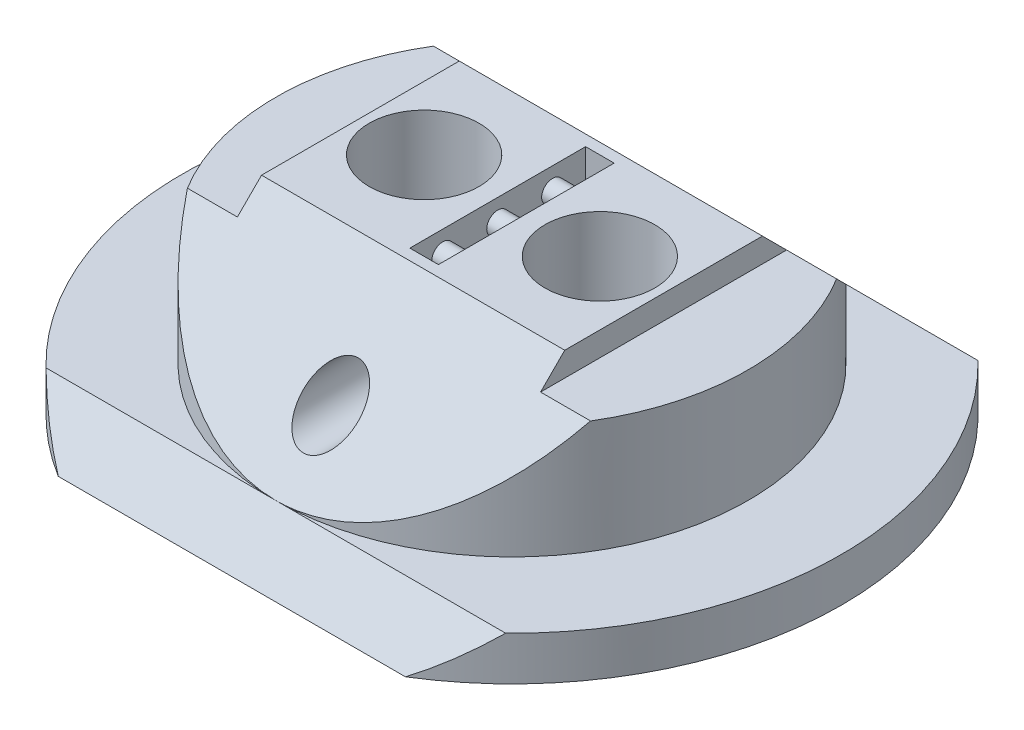
SolidWorks part; units mm, degrees
ref_plane "Front Plane" through (0, 0, 0) normal (0, 0, 1) x (1, 0, 0)
ref_plane "Top Plane" through (0, 0, 0) normal (0, 1, 0) x (1, 0, 0)
ref_plane "Right Plane" through (0, 0, 0) normal (1, 0, 0) x (0, 0, -1)
sketch "Sketch1" plane through (0, 0, 0) normal (0, 1, 0) x (1, 0, 0)
  circle A0 centre (0, 0) radius 30
extrude "Boss-Extrude1" add sketch "Sketch1" along normal blind 4
sketch "Sketch2" plane through (0, 0, 0) normal (1, 0, 0) x (0, 0, -1)
  line L0 (0, 4) -> (21.5, 4)
  line L1 (30, 4) -> (-30, 4) construction
  line L3 (0, 4) -> (-21.5, 4)
  line L5 (0, 4) -> (0, 19.5) construction
  line L6 (-9, 16.5) -> (-21.5, 4)
  line L7 (-9, 16.5) -> (9, 16.5)
  line L9 (9, 16.5) -> (21.5, 4)
  dimension "D1" = 12.5
  dimension "D2" = 45
  dimension "D3" = 21.5
  dimension "D4" = 21.5
  dimension "D5" = 45
sketch "Sketch3" plane through (0, 4, 0) normal (0, 1, 0) x (1, 0, 0)
  circle A0 centre (0, 0) radius 21.5
  dimension "D1" = 43
extrude "Boss-Extrude2" add sketch "Sketch2" along normal up to surface and the other way up to surface up to face at (0, 4, 30) other way up to face at (0, 4, 30)
ref_plane "Plane1" through (0, 12.75, -12.75) normal (0, 0.7071, -0.7071) x (1, 0, 0)
other "SurfaceCut1"
ref_plane "Plane2" through (0, 12.75, 12.75) normal (0, 0.7071, 0.7071) x (1, 0, 0)
other "SurfaceCut2"
extrude "Cut-Extrude2" cut sketch "Sketch3" against normal up to surface (12.5 mm away) flip side to cut contours A0
sketch "Sketch5" plane through (0, 0, 0) normal (0, -1, 0) x (-1, 0, 0)
  line L0 (0, 0) -> (0, -6)
  line L1 (0, -6) -> (-17.5, -6)
  line L2 (-17.5, -6) -> (-17.5, 6)
  line L3 (-17.5, 6) -> (17.5, 6)
  line L4 (17.5, 6) -> (17.5, -6)
  line L5 (17.5, -6) -> (0, -6)
  circle A0 centre (0, 0) radius 6
  circle A1 centre (0, 0) radius 3.5
  dimension "D1" = 12
  dimension "D2" = 7
  dimension "D3" = 12
  dimension "D4" = 6
  dimension "D5" = 35
  dimension "D6" = 17.5
extrude "Boss-Extrude3" add sketch "Sketch5" along normal blind 18 contours L1 L2 L3 L4 L5
sketch "Sketch6" plane through (0, 0, 0) normal (0, -1, 0) x (1, 0, 0)
  line L0 (0, 6) -> (0, 15) construction
  line L1 (-17.5, 6) -> (17.5, 6) construction
  line L2 (0, 15) -> (7, 15)
  line L3 (7, 15) -> (7, 6)
  line L4 (-17.5, 6) -> (17.5, 6) construction
  line L5 (7, 6) -> (-7, 6)
  line L6 (-7, 6) -> (-7, 15)
  line L7 (-7, 15) -> (0, 15)
  dimension "D1" = 14
  dimension "D2" = 9
extrude "Boss-Extrude4" add sketch "Sketch6" along normal blind 15 contours L7 L2 L3 L5 L6
sketch "Sketch7" plane through (0, 0, 0) normal (0, -1, 0) x (1, 0, 0)
  line L0 (0, -6) -> (0, -15) construction
  line L1 (17.5, -6) -> (-17.5, -6) construction
  line L2 (0, -15) -> (7, -15)
  line L3 (7, -15) -> (7, -6)
  line L4 (7, -6) -> (-7, -6)
  line L7 (-7, -6) -> (-7, -15)
  line L8 (-7, -15) -> (0, -15)
  dimension "D1" = 9
  dimension "D2" = 14
extrude "Boss-Extrude5" add sketch "Sketch7" along normal blind 15
sketch "Sketch8" plane through (0, 0, 0) normal (0, 0, 1) x (1, 0, 0)
  line L0 (0, 0) -> (12.5, 0) construction
  line L1 (12.5, 0) -> (12.5, -12.5) construction
  line L2 (12.5, -12.5) -> (-12.5, -12.5) construction
  line L3 (-12.5, -12.5) -> (-12.5, 0) construction
  line L4 (-12.5, 0) -> (0, 0) construction
  circle A0 centre (-12.5, -12.5) radius 2
  circle A1 centre (12.5, -12.5) radius 2
  dimension "D4" = 4
  dimension "D5" = 4
  dimension "D1" = 12.5
  dimension "D2" = 25
  dimension "D3" = 12.5
extrude "Cut-Extrude3" cut sketch "Sketch8" against normal through all both and the other way through all contours A0 | A1
ref_plane "Plane3" through (0, -18, 0) normal (0, -1, 0) x (-1, 0, 0)
ref_plane "Plane4" through (10.366, -9.6749, -8.0624) normal (0.6355, -0.5931, -0.4943) x (-0.3613, 0.3373, -0.8693)
ref_plane "Plane5" through (-10.366, -9.6749, -8.0624) normal (0.6355, 0.5931, 0.4943) x (0.3613, 0.3373, -0.8693)
ref_plane "Plane6" through (10.366, -9.6749, 8.0624) normal (-0.6355, 0.5931, -0.4943) x (-0.3613, 0.3373, 0.8693)
ref_plane "Plane7" through (-10.366, -9.6749, 8.0624) normal (0.6355, 0.5931, -0.4943) x (-0.3613, -0.3373, -0.8693)
ref_plane "Plane9" through (0, 0, 6) normal (0, 0, 1) x (1, 0, 0)
sketch "Sketch16" plane through (0, 0, 6) normal (0, 0, 1) x (1, 0, 0)
  line L0 (17.5, -18) -> (17.5, -14.5)
  line L1 (-6.6, -18) -> (6.6, -18) construction
  line L2 (17.5, -18) -> (17.5, 0) construction
  line L3 (17.5, -18) -> (14, -18)
  line L4 (17.5, -14.5) -> (14, -18)
  line L5 (-17.5, -18) -> (-14, -18)
  line L6 (-17.5, -18) -> (-17.5, 0) construction
  line L7 (-14, -18) -> (-17.5, -14.5)
  line L8 (-17.5, -14.5) -> (-17.5, -18)
  dimension "D2" = 3.5
extrude "Cut-Extrude8" cut sketch "Sketch16" against normal through all both and the other way through all
sketch "Sketch17" plane through (10.366, -9.6749, -8.0624) normal (0.6355, -0.5931, -0.4943) x (-0.3613, 0.3373, -0.8693)
  line L0 (-2.3725, -6.1896) -> (7.9806, -0.7067)
  line L1 (5.4512, -6.1896) -> (10.5101, 4.7762) construction
  line L2 (7.9806, -0.7067) -> (7.9806, -10.9658)
  line L3 (10.5101, -15.7421) -> (5.4512, -6.1896) construction
  line L4 (7.9806, -10.9658) -> (-2.3725, -6.1896)
extrude "Cut-Extrude9" cut sketch "Sketch17" along normal through all
sketch "Sketch19" plane through (-10.366, -9.6749, -8.0624) normal (0.6355, 0.5931, 0.4943) x (0.3613, 0.3373, -0.8693)
  line L0 (-2.3725, -6.1896) -> (7.9806, -10.9658)
  line L1 (7.9806, -10.9658) -> (7.9806, -0.7067)
  line L2 (5.4512, -6.1896) -> (10.5101, 4.7762) construction
  line L3 (7.9806, -0.7067) -> (-2.3725, -6.1896)
extrude "Cut-Extrude11" cut sketch "Sketch19" against normal blind 20 contours L3 L0 L1
sketch "Sketch20" plane through (-10.366, -9.6749, 8.0624) normal (0.6355, 0.5931, -0.4943) x (-0.3613, -0.3373, -0.8693)
  line L0 (2.3725, -6.1896) -> (-7.9806, -0.7067)
  line L1 (-5.4512, -6.1896) -> (-10.5101, 4.7762) construction
  line L2 (-7.9806, -0.7067) -> (-7.9806, -10.9658)
  line L3 (-5.4512, -6.1896) -> (-10.5101, -15.7421) construction
  line L4 (-7.9806, -10.9658) -> (2.3725, -6.1896)
extrude "Cut-Extrude12" cut sketch "Sketch20" against normal blind 20
sketch "Sketch21" plane through (10.366, -9.6749, 8.0624) normal (-0.6355, 0.5931, -0.4943) x (-0.3613, 0.3373, 0.8693)
  line L0 (-2.3725, -6.1896) -> (7.9806, -0.7067)
  line L1 (5.4512, -6.1896) -> (10.5101, 4.7762) construction
  line L2 (7.9806, -0.7067) -> (7.9806, -10.9658)
  line L3 (7.9806, -10.9658) -> (-2.3725, -6.1896)
extrude "Cut-Extrude13" cut sketch "Sketch21" against normal blind 20 contours L0 L2 L3
ref_plane "Plane10" through (0, 16.5, 0) normal (0, 1, 0) x (1, 0, 0)
sketch "Sketch25" plane through (0, 0, 0) normal (0, 0, 1) x (1, 0, 0)
  line L1 (-33.0377, 0) -> (33.0377, 0)
  line L2 (-33.0377, 0) -> (-33.0377, -20.1422)
  line L3 (-33.0377, -20.1422) -> (33.0377, -20.1422)
  line L4 (33.0377, 0) -> (33.0377, -20.1422)
  dimension "D1" = 20.1422
  dimension "D2" = 66.0754
extrude "Cut-Extrude14" cut sketch "Sketch25" along normal through all both and the other way through all
sketch "Sketch26" plane through (0, 16.5, 0) normal (0, 1, 0) x (1, 0, 0)
  line L0 (-9.075, 0) -> (9.075, 0) construction
  circle A0 centre (-8, 0) radius 5
  circle A2 centre (8, 0) radius 5
  dimension "D1" = 10
  dimension "D2" = 10
  dimension "D3" = 8
  dimension "D4" = 8
extrude "Cut-Extrude15" cut sketch "Sketch26" against normal blind 24
sketch "Sketch29" plane through (0, 0, 6) normal (0, 0, 1) x (1, 0, 0)
  line L0 (21.5, 4) -> (21.5, 16.5) construction
  line L1 (21.5, 14.3) -> (13.8, 14.3)
  line L2 (21.5, 14.3) -> (21.5, 16.5)
  line L3 (21.5, 16.5) -> (13.8, 16.5)
  line L4 (13.8, 14.3) -> (13.8, 16.5)
  line L5 (9.9, 16.5) -> (-9.9, 16.5) construction
  dimension "D1" = 2.2
  dimension "D2" = 7.7
extrude "Cut-Extrude17" cut sketch "Sketch29" against normal through all both and the other way through all
sketch "Sketch31" plane through (0, 0, 6) normal (0, 0, 1) x (1, 0, 0)
  line L0 (-21.5, 16.5) -> (-21.5, 4) construction
  line L1 (-21.5, 14.3) -> (-13.8, 14.3)
  line L2 (-21.5, 14.3) -> (-21.5, 16.5)
  line L3 (-21.5, 16.5) -> (-13.8, 16.5)
  line L4 (-13.8, 14.3) -> (-13.8, 16.5)
  line L5 (9.9, 16.5) -> (-9.9, 16.5) construction
  dimension "D1" = 2.2
  dimension "D2" = 7.7
extrude "Cut-Extrude18" cut sketch "Sketch31" against normal through all both and the other way through all
sketch "Sketch33" plane through (0, 0, 0) normal (0, 0, 1) x (1, 0, 0)
  line L0 (0, -9.075) -> (0, 9.075) construction
  line L1 (-15.8035, 0) -> (15.8035, 0) construction
  circle A0 centre (0, 9) radius 2.5
  dimension "D1" = 5
  dimension "D2" = 9
extrude "Cut-Extrude20" cut sketch "Sketch33" against normal through all both and the other way through all
sketch "Sketch34" plane through (0, 0, 0) normal (0, -1, 0) x (1, 0, 0)
  circle A0 centre (0, 0) radius 1.5
  dimension "D1" = 3
extrude "Cut-Extrude21" cut sketch "Sketch34" against normal blind 10
sketch "Sketch35" plane through (0, 16.5, 0) normal (0, 1, 0) x (1, 0, 0)
  line L0 (13.8, 9) -> (-13.8, 9) construction
  line L1 (-1.3, 8) -> (1.3, 8)
  line L2 (-1.3, 8) -> (-1.3, -8)
  line L3 (-1.3, -8) -> (1.3, -8)
  line L4 (1.3, 8) -> (1.3, -8)
  line L5 (13.8, -9) -> (-13.8, -9) construction
  line L6 (13.8, 9) -> (13.8, -9) construction
  line L7 (-13.8, 11.2) -> (-13.8, -11.2) construction
  dimension "D1" = 1
  dimension "D2" = 1
  dimension "D3" = 12.5
  dimension "D4" = 12.5
extrude "Cut-Extrude23" cut sketch "Sketch35" against normal blind 4
sketch "Sketch37" plane through (-1.3, 0, 0) normal (1, 0, 0) x (0, 0, -1)
  line L0 (-8, 16.5) -> (8, 16.5) construction
  line L1 (0, 9.075) -> (0, -9.075) construction
  circle A0 centre (-5, 14.5) radius 1
  circle A1 centre (0, 14.5) radius 1
  circle A2 centre (5, 14.5) radius 1
  dimension "D1" = 2
  dimension "D2" = 2
  dimension "D3" = 2
  dimension "D4" = 2
  dimension "D5" = 2
  dimension "D6" = 2
  dimension "D7" = 0
  dimension "D8" = 5
  dimension "D9" = 5
extrude "Boss-Extrude6" add sketch "Sketch37" along normal up to next
